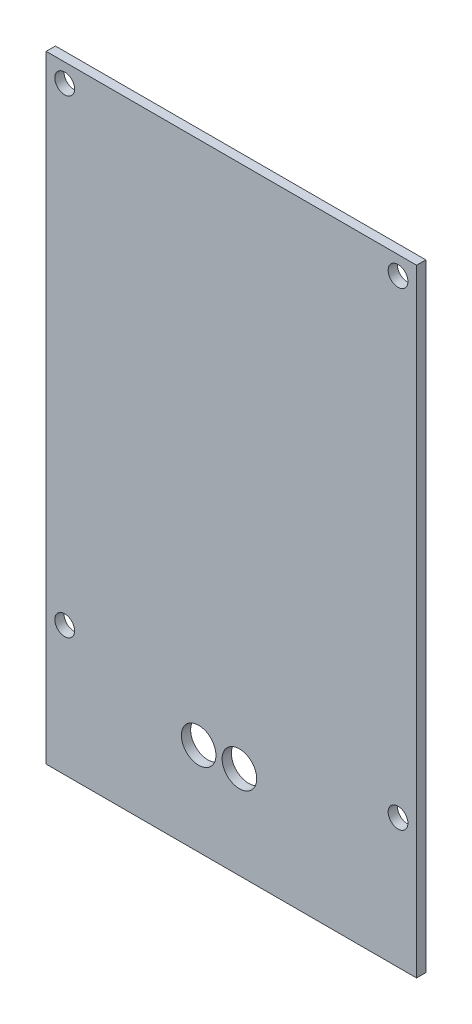
SolidWorks part; units mm, degrees
ref_plane "Front Plane" through (0, 0, 0) normal (0, 0, 1) x (1, 0, 0)
ref_plane "Top Plane" through (0, 0, 0) normal (0, 1, 0) x (1, 0, 0)
ref_plane "Right Plane" through (0, 0, 0) normal (1, 0, 0) x (0, 0, -1)
sketch "Sketch1" plane through (0, 0, 0) normal (0, 0, 1) x (1, 0, 0)
  line L0 (0, 0) -> (0, 97.3033) construction
  line B0 (-30, 78.447) -> (30, 78.447)
  line B1 (30, 78.447) -> (30, -21.553)
  line B2 (-30, -21.553) -> (-30, 78.447)
  circle B3 centre (-5.3, -6.553) radius 2.8
  circle B4 centre (-27, -0.553) radius 1.6
  circle B5 centre (27, 75.447) radius 1.6
  line B6 (30, -21.553) -> (-30, -21.553)
  circle B7 centre (-27, 75.447) radius 1.6
  circle B8 centre (27, -0.553) radius 1.6
  circle B9 centre (1.3, -6.553) radius 2.8
sketch_block_instance "PCB_Edge-1"
sketch_block "PCB_Edge" parameters "D1"=97.3033
extrude "Boss-Extrude1" add sketch "Sketch1" along normal blind 1.5
